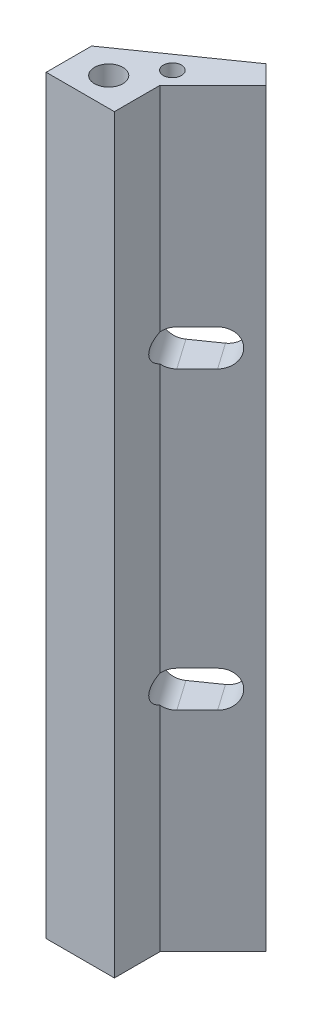
SolidWorks part; units mm, degrees
material "6061 Alloy"
ref_plane "Front Plane" through (0, 0, 0) normal (0, 0, 1) x (1, 0, 0)
ref_plane "Top Plane" through (0, 0, 0) normal (0, 1, 0) x (1, 0, 0)
ref_plane "Right Plane" through (0, 0, 0) normal (1, 0, 0) x (0, 0, -1)
ref_plane "Plane1" through (0, 66, 0) normal (0, 1, 0) x (1, 0, 0)
sketch "Sketch1" plane through (0, 66, 0) normal (0, 1, 0) x (1, 0, 0)
  line L0 (3.8298, 1.2829) -> (-5.1808, -5.0264)
  line L1 (-5.1808, -5.0264) -> (-5.1808, -9.0264)
  line L2 (-5.1808, -9.0264) -> (0.8192, -9.0264)
  line L3 (0.8192, -9.0264) -> (0.8192, -5.0264)
  line L4 (0.8192, -5.0264) -> (5.4792, -0.3664)
  line L5 (5.4792, -0.3664) -> (3.8298, 1.2829)
  dimension "D1" = 6
  dimension "D2" = 4
  dimension "D4" = 11
  dimension "D5" = 125
  dimension "D6" = 135
extrude "Boss-Extrude1" add sketch "Sketch1" against normal blind 66
sketch "Sketch2" plane through (2.9228, 0, 2.9228) normal (0.7071, 0, 0.7071) x (0.7071, 0, -0.7071)
  line L0 (0.6176, 47.6) -> (-2.3824, 47.6)
  line L1 (-2.3824, 44.4) -> (0.6176, 44.4)
  arc A0 (-2.3824, 47.6) -> (-2.3824, 44.4) centre (-2.3824, 46) ccw
  arc A1 (0.6176, 44.4) -> (0.6176, 47.6) centre (0.6176, 46) ccw
  dimension "D1" = 3
sketch "Sketch3" plane through (2.9228, 0, 2.9228) normal (0.7071, 0, 0.7071) x (0.7071, 0, -0.7071)
  line L0 (0.6176, 21.6) -> (-2.3824, 21.6)
  line L1 (-2.3824, 18.4) -> (0.6176, 18.4)
  arc A0 (-2.3824, 21.6) -> (-2.3824, 18.4) centre (-2.3824, 20) ccw
  arc A1 (0.6176, 18.4) -> (0.6176, 21.6) centre (0.6176, 20) ccw
  dimension "D1" = 3
hole_wizard "M3x0.5 Tapped Hole1" positions "Sketch5" profile "Sketch4" tap size "M3x0.5" standard "ANSI Metric"
sketch "Sketch5" plane through (0, 0, 0) normal (0, -1, 0) x (-1, 0, 0)
  line L1 (5.1808, -5.0264) -> (5.1808, -9.0264) construction
  point P0 (2.1808, -6.5264)
  dimension "D1" = 1.5
  dimension "D2" = 3
sketch "Sketch4" plane through (-2.1808, 0, 6.5264) normal (1, 0, 0) x (0, 0, -1)
  line L0 (0, 0) -> (0, 8.2511)
  line L1 (0, 8.2511) -> (1.25, 7.5)
  line L2 (1.25, 7.5) -> (1.25, 0)
  line L5 (1.25, 0) -> (0, 0)
  line L10 (0, 8.2511) -> (-1.25, 7.5) construction
  line L11 (0, -6.35) -> (0, 107.95) construction
  dimension "Tap Drill Dia." = 2.5
  dimension "Tap Drill Depth" = 7.5
  dimension "Drill Angle" = 118
hole_wizard "M2x0.4 Tapped Hole1" positions "Sketch7" profile "Sketch6" tap size "M2x0.4" standard "ANSI Metric"
sketch "Sketch7" plane through (0, 0, 0) normal (0, -1, 0) x (-1, 0, 0)
  line L3 (5.1808, -5.0264) -> (5.1808, -9.0264) construction
  point P0 (-0.2192, -3.3264)
  dimension "D1" = 5.4
  dimension "D2" = 1.7
sketch "Sketch6" plane through (0.2192, 0, 3.3264) normal (1, 0, 0) x (0, 0, -1)
  line L0 (0, 0) -> (0, 5.6807)
  line L1 (0, 5.6807) -> (0.8, 5.2)
  line L2 (0.8, 5.2) -> (0.8, 0)
  line L5 (0.8, 0) -> (0, 0)
  line L10 (0, 5.6807) -> (-0.8, 5.2) construction
  line L11 (0, -6.35) -> (0, 107.95) construction
  dimension "Tap Drill Dia." = 1.6
  dimension "Tap Drill Depth" = 5.2
  dimension "Drill Angle" = 118
sketch "Sketch9" plane through (0, 66, 0) normal (0, 1, 0) x (1, 0, 0)
  point P0 (-2.1808, -6.5264)
  point P1 (0.2192, -3.3264)
hole_wizard "M3x0.5 Tapped Hole2" positions "3DSketch2" profile "Sketch10" tap size "M3x0.5" standard "ANSI Metric"
sketch3d "3DSketch2"
  point P0 (-2.1808, 66, 6.5264)
sketch "Sketch10" plane through (-2.1808, 66, 6.5264) normal (1, 0, 0) x (0, 0, 1)
  line L0 (0, 0) -> (0, 8.2511)
  line L1 (0, 8.2511) -> (1.25, 7.5)
  line L2 (1.25, 7.5) -> (1.25, 0)
  line L5 (1.25, 0) -> (0, 0)
  line L10 (0, 8.2511) -> (-1.25, 7.5) construction
  line L11 (0, -6.35) -> (0, 107.95) construction
  dimension "Tap Drill Dia." = 2.5
  dimension "Tap Drill Depth" = 7.5
  dimension "Drill Angle" = 118
hole_wizard "M2x0.4 Tapped Hole2" positions "3DSketch3" profile "Sketch11" tap size "M2x0.4" standard "ANSI Metric"
sketch3d "3DSketch3"
  point P0 (0.2192, 66, 3.3264)
sketch "Sketch11" plane through (0.2192, 66, 3.3264) normal (1, 0, 0) x (0, 0, 1)
  line L0 (0, 0) -> (0, 5.6807)
  line L1 (0, 5.6807) -> (0.8, 5.2)
  line L2 (0.8, 5.2) -> (0.8, 0)
  line L5 (0.8, 0) -> (0, 0)
  line L10 (0, 5.6807) -> (-0.8, 5.2) construction
  line L11 (0, -6.35) -> (0, 107.95) construction
  dimension "Tap Drill Dia." = 1.6
  dimension "Tap Drill Depth" = 5.2
  dimension "Drill Angle" = 118
sketch "Sketch12" plane through (0.6572, 0, 0.9386) normal (-0.5736, 0, -0.8192) x (-0.8192, 0, 0.5736)
  line L0 (-1.326, 44.4) -> (1.174, 44.4)
  line L1 (-1.326, 47.6) -> (1.174, 47.6)
  line L2 (-3.8731, 33) -> (7.1269, 33) construction
  line L3 (-3.8731, 0) -> (-3.8731, 66) construction
  line L4 (7.1269, 0) -> (7.1269, 66) construction
  line L5 (-1.326, 18.4) -> (1.174, 18.4)
  line L6 (-1.326, 21.6) -> (1.174, 21.6)
  arc A0 (-1.326, 47.6) -> (-1.326, 44.4) centre (-1.326, 46) ccw
  arc A1 (1.174, 47.6) -> (1.174, 44.4) centre (1.174, 46) cw
  arc A2 (-1.326, 18.4) -> (-1.326, 21.6) centre (-1.326, 20) cw
  arc A3 (1.174, 21.6) -> (1.174, 18.4) centre (1.174, 20) cw
  dimension "D1" = 2.5
extrude "Cut-Extrude1" cut sketch "Sketch12" against normal through all
